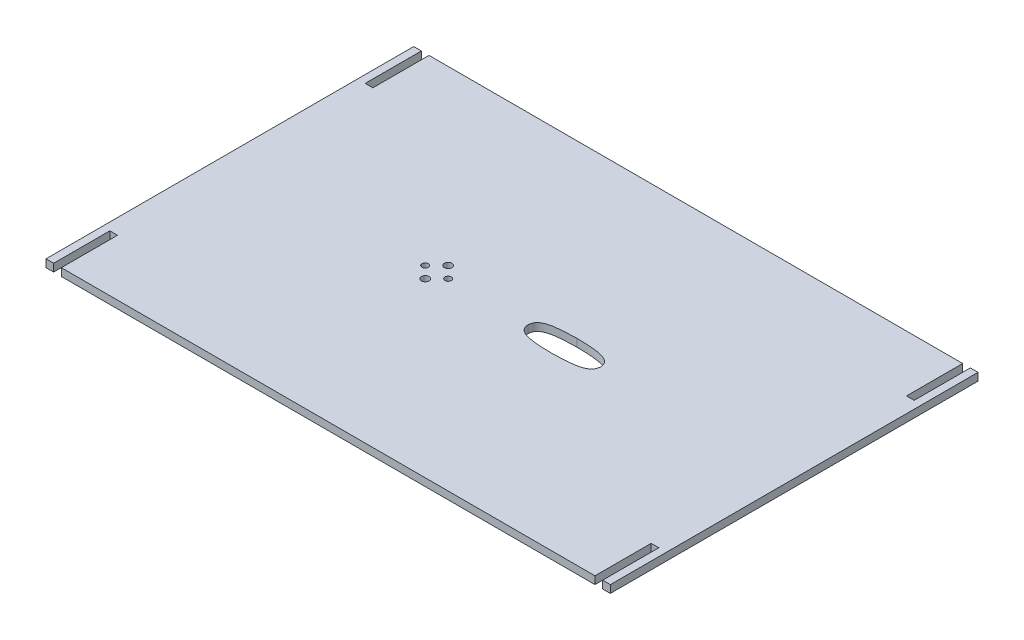
SolidWorks part; units mm, degrees
ref_plane "Front" through (0, 0, 0) normal (0, 0, 1) x (1, 0, 0)
ref_plane "Top" through (0, 0, 0) normal (0, 1, 0) x (1, 0, 0)
ref_plane "Right" through (0, 0, 0) normal (1, 0, 0) x (0, 0, -1)
sketch "Sketch1" plane through (0, 0, 0) normal (0, 1, 0) x (1, 0, 0)
  line L0 (418, 244) -> (424, 244)
  line L1 (0, 0) -> (418, 0)
  line L3 (0, 288) -> (418, 288)
  line L6 (424, 44) -> (418, 44)
  line L7 (418, 0) -> (418, 44)
  line L8 (418, 244) -> (418, 288)
  line L9 (0, 288) -> (0, 244)
  line L10 (-6, 244) -> (-6, 288)
  line L11 (0, 244) -> (-6, 244)
  line L12 (-6, 288) -> (-12, 288)
  line L14 (-6, 44) -> (0, 44)
  line L15 (0, 44) -> (0, 0)
  line L17 (-12, 288) -> (-12, 0)
  line L19 (-6, 44) -> (-6, 0)
  line L20 (-6, 0) -> (-12, 0)
  line L21 (424, 244) -> (424, 288)
  line L22 (424, 288) -> (430, 288)
  line L23 (430, 288) -> (430, 0)
  line L24 (430, 0) -> (424, 0)
  line L26 (424, 0) -> (424, 44)
  dimension "D1" = 6
  dimension "D2" = 6
  dimension "D3" = 6
  dimension "D4" = 288
  dimension "D5" = 418
  dimension "D6" = 200
  dimension "D7" = 12
  dimension "D8" = 430
  dimension "D9" = 12
  dimension "D10" = 44
  dimension "D11" = 6
extrude "Boss-Extrude1" add sketch "Sketch1" along normal blind 6
sketch "Sketch2" plane through (0, 6, 0) normal (0, 1, 0) x (1, 0, 0)
  line L0 (418, 288) -> (0, 288) construction
  line L1 (150, 153) -> (150, 135) construction
  line L2 (141, 144) -> (159, 144) construction
  line L3 (430, 0) -> (430, 288) construction
  line L4 (221.5, 144) -> (250, 144) construction
  line L5 (221.5, 154) -> (278.5, 154) construction
  line L6 (221.5, 154) -> (221.5, 134) construction
  line L7 (221.5, 134) -> (278.5, 134) construction
  line L8 (278.5, 154) -> (278.5, 134) construction
  line L9 (221.5, 154) -> (278.5, 134) construction
  line L10 (221.5, 134) -> (278.5, 154) construction
  line L11 (250, 144) -> (250, 154) construction
  circle A1 centre (150, 135) radius 3
  circle A2 centre (150, 153) radius 3
  circle A3 centre (141, 144) radius 2.5
  circle A4 centre (159, 144) radius 2.5
  spline S0 degree 3 poles (250, 154) (231.9785, 153.6663) (221.9333, 152.4469) (221.5, 144) knots 0 0 0 0 1 1 1 1
  spline S1 degree 3 poles (250, 154) (268.0215, 153.6663) (278.0667, 152.4469) (278.5, 144) knots 0 0 0 0 1 1 1 1
  spline S2 degree 3 poles (250, 134) (268.0215, 134.3337) (278.0667, 135.5531) (278.5, 144) knots 0 0 0 0 1 1 1 1
  spline S3 degree 3 poles (250, 134) (231.9785, 134.3337) (221.9333, 135.5531) (221.5, 144) knots 0 0 0 0 1 1 1 1
  point P0 (150, 144)
  point P9 (250, 144)
  dimension "D1" = 9
  dimension "D4" = 6
  dimension "D5" = 5
  dimension "D7" = 18
  dimension "D8" = 144
  dimension "D9" = 57
  dimension "D10" = 20
  dimension "D3" = 9
  dimension "D11" = 180
  dimension "D2" = 280
  dimension "D6" = 18
extrude "Cut-Extrude1" cut sketch "Sketch2" against normal blind 6
